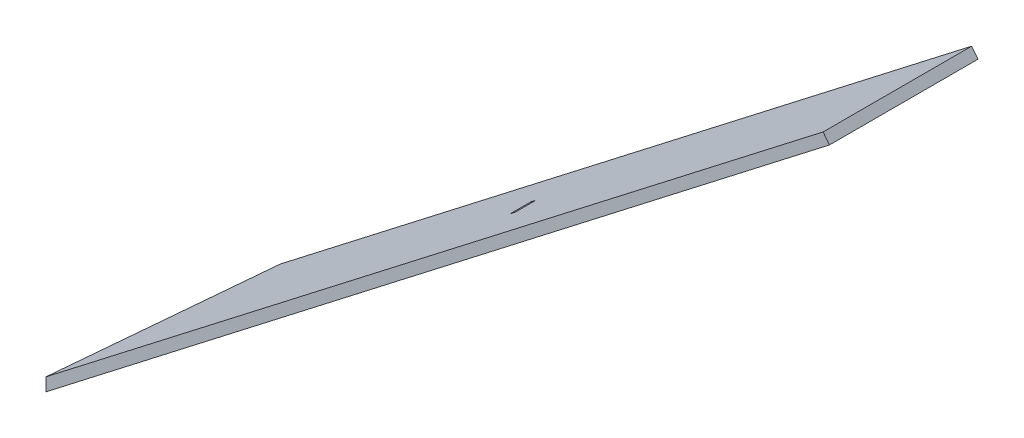
SolidWorks part; units mm, degrees
material "white foam"
ref_plane "Front Plane" through (0, 0, 0) normal (0, 0, 1) x (1, 0, 0)
ref_plane "Top Plane" through (0, 0, 0) normal (0, 1, 0) x (1, 0, 0)
ref_plane "Right Plane" through (0, 0, 0) normal (1, 0, 0) x (0, 0, -1)
sketch "Sketch1" plane through (0, 0, 0) normal (0, 0, 1) x (1, 0, 0)
  line L0 (0, 0) -> (380.0247, 293.7164)
  line L1 (0, 0) -> (-380.0247, 293.7164)
  line L2 (-380.0247, 0) -> (380.0247, 0) construction
  line L3 (0, 6.3193) -> (376.967, 297.6726)
  line L4 (0, 6.3193) -> (-376.967, 297.6726)
  line L5 (380.0247, 293.7164) -> (376.967, 297.6726)
  line L6 (-380.0247, 293.7164) -> (-376.967, 297.6726)
  point P7 (0, 0)
  dimension "D1" = 37.7
  dimension "D2" = 37.7
  dimension "D3" = 480.3
  dimension "D4" = 5
extrude "Boss-Extrude1" add sketch "Sketch1" against normal blind 240.2
sketch "Sketch2" plane through (0, 0, 0) normal (0, 1, 0) x (1, 0, 0)
  line L0 (-380.0247, 240.2) -> (-380.0247, 0) construction
  line L1 (380.0247, 240.2) -> (-380.0247, 240.2)
  line L2 (380.0247, 240.2) -> (380.0247, 168.14)
  line L3 (380.0247, 168.14) -> (-380.0247, 168.14)
  line L4 (-380.0247, 240.2) -> (-380.0247, 168.14)
  dimension "D1" = 72.06
extrude "Cut-Extrude3" cut sketch "Sketch2" along normal through all both and the other way through all flip side to cut contours L1 L4 L3 L2
sketch "Sketch3" plane through (0, 0, 0) normal (0, 1, 0) x (1, 0, 0)
  line L0 (0, 168.14) -> (41.6039, 240.2)
  line L1 (376.967, 240.2) -> (0, 240.2) construction
  line L2 (41.6039, 240.2) -> (-41.6039, 240.2)
  line L3 (-41.6039, 240.2) -> (0, 168.14)
  line L4 (0, 240.2) -> (0, 168.14) construction
  line L9 (380.0247, 168.14) -> (380.0247, 240.2)
  line L10 (0, 168.14) -> (380.0247, 168.14)
  line L11 (0, 240.2) -> (0, 168.14)
  line L12 (380.0247, 240.2) -> (0, 240.2)
  line L13 (380.0247, 168.14) -> (380.0247, 240.2)
  line L14 (0, 168.14) -> (380.0247, 168.14)
  line L16 (380.0247, 240.2) -> (0, 240.2)
  line L17 (0, 168.14) -> (0, 240.2)
  line L18 (-380.0247, 168.14) -> (0, 168.14)
  line L19 (-380.0247, 240.2) -> (-380.0247, 168.14)
  line L20 (0, 240.2) -> (-380.0247, 240.2)
  line L22 (-380.0247, 168.14) -> (0, 168.14)
  line L23 (-380.0247, 240.2) -> (-380.0247, 168.14)
  line L24 (0, 240.2) -> (-380.0247, 240.2)
  dimension "D1" = 60
  dimension "D2" = 30
  dimension "D3" = 0
  dimension "D4" = 0
extrude "Cut-Extrude4" cut sketch "Sketch3" along normal through all contours L2 L3 L0 | L3 L24 L23 L22
sketch "Sketch4" plane through (-3.0576, 3.9561, 0) normal (-0.6115, 0.7912, 0) x (0.7912, 0.6115, 0)
  line L0 (242.0822, 168.14) -> (242.0822, 240.2) construction
  line L1 (3.8644, 168.14) -> (480.3, 168.14) construction
  line L2 (480.3, 240.2) -> (56.4461, 240.2) construction
  line L4 (249.2822, 199.17) -> (252.2822, 199.17)
  line L5 (249.2822, 199.17) -> (249.2822, 209.17)
  line L6 (249.2822, 209.17) -> (252.2822, 209.17)
  line L7 (252.2822, 199.17) -> (252.2822, 209.17)
  point P10 (249.2822, 204.17)
  point P11 (242.0822, 204.17)
  dimension "D1" = 10
  dimension "D2" = 3
  dimension "D3" = 7.2
extrude "Cut-Extrude5" cut sketch "Sketch4" against normal through all both and the other way through all
sketch "Sketch5" plane through (0, 0, 0) normal (0.6115, -0.7912, 0) x (0.7912, 0.6115, 0)
  line L0 (480.3, -204.17) -> (30.1553, -204.17) construction
  line L3 (480.3, -240.2) -> (480.3, -168.14) construction
  line L6 (56.4461, -240.2) -> (3.8644, -168.14) construction
  line B0 (440.3, -204.17) -> (295.3, -204.17) construction
  line B1 (205.3, -225.2) -> (75.3, -225.2)
  arc B2 (75.3, -183.14) -> (75.3, -225.2) centre (75.3, -204.17) ccw
  line B3 (205.3, -183.14) -> (75.3, -183.14)
  arc B4 (205.3, -225.2) -> (205.3, -183.14) centre (205.3, -204.17) ccw
  line B5 (440.3, -225.2) -> (295.3, -225.2)
  arc B6 (295.3, -183.14) -> (295.3, -225.2) centre (295.3, -204.17) ccw
  line B7 (440.3, -183.14) -> (295.3, -183.14)
  arc B8 (440.3, -225.2) -> (440.3, -183.14) centre (440.3, -204.17) ccw
  dimension "D1" = 40
sketch_block_instance "Block1-1"
sketch_block "Block1" parameters "D1"=145, "D2"=90, "D3"=130
extrude "Cut-Extrude7" [suppressed] cut sketch "Sketch5" against normal blind 10
equation "\"D3@Sketch4\"=12.4/2+1"
equation "\"D3@Sketch1\"=960.6/2"
equation "\"D1@Boss-Extrude1\"=240.2"
